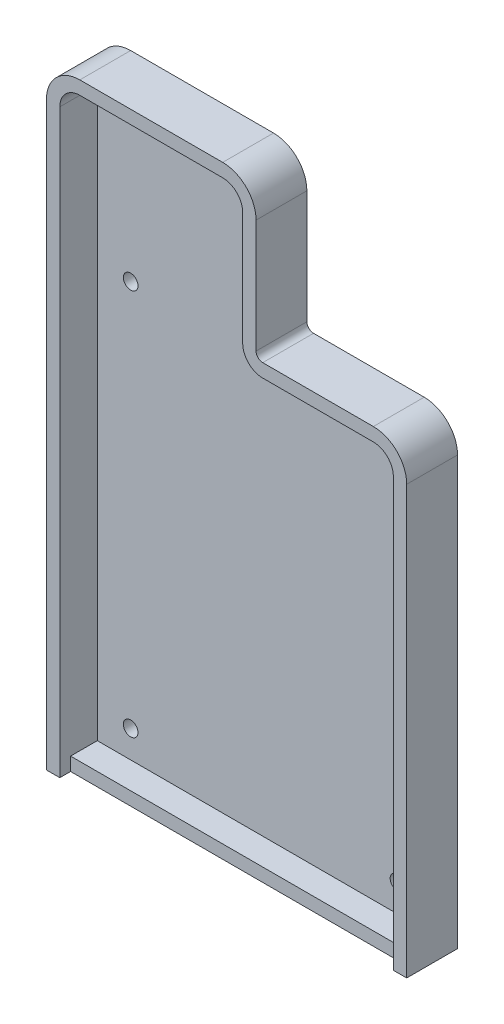
SolidWorks part; units mm, degrees
ref_plane "Front Plane" through (0, 0, 0) normal (0, 0, 1) x (1, 0, 0)
ref_plane "Top Plane" through (0, 0, 0) normal (0, 1, 0) x (1, 0, 0)
ref_plane "Right Plane" through (0, 0, 0) normal (1, 0, 0) x (0, 0, -1)
ref_plane "Plane1" through (200, 247, 0) normal (0, 1, 0) x (1, 0, 0)
sketch "Sketch3" plane through (0, 0, 0) normal (0, 0, 1) x (1, 0, 0)
  line L0 (200, 60) -> (200, 247) construction
  line L1 (200, 161.9071) -> (250, 161.9071)
  line L2 (250, 224) -> (250, 60) construction
  line L3 (227.416, 247) -> (227.416, 230) construction
  line L4 (230.416, 227) -> (247, 227) construction
  line L5 (227.416, 247) -> (227.416, 230)
  line L6 (230.416, 227) -> (247, 227)
  line L7 (203, 250) -> (224.416, 250) construction
  line L8 (250, 224) -> (250, 161.9071)
  line L9 (200, 161.9071) -> (200, 247)
  line L10 (203, 250) -> (224.416, 250)
  line L11 (252, 224.0004) -> (252, 159.9071)
  line L12 (198, 159.9071) -> (252, 159.9071)
  line L13 (198, 159.9071) -> (198, 247.0004)
  line L14 (202.9996, 252) -> (224.4164, 252)
  line L15 (229.416, 247.0004) -> (229.416, 230.0004)
  line L16 (230.4164, 229) -> (247.0004, 229)
  arc A0 (227.416, 230) -> (230.416, 227) centre (230.4171, 230.0011) ccw construction
  arc A1 (250, 224) -> (247, 227) centre (246.9989, 223.9989) ccw construction
  arc A2 (227.416, 230) -> (230.416, 227) centre (230.4171, 230.0011) ccw
  arc A3 (250, 224) -> (247, 227) centre (246.9989, 223.9989) ccw
  arc A4 (203, 250) -> (200, 247) centre (203.0011, 246.9989) ccw construction
  arc A5 (227.416, 247) -> (224.416, 250) centre (224.4149, 246.9989) ccw construction
  arc A6 (203, 250) -> (200, 247) centre (203.0011, 246.9989) ccw
  arc A7 (227.416, 247) -> (224.416, 250) centre (224.4149, 246.9989) ccw
  arc A8 (202.9996, 252) -> (198, 247.0004) centre (203.0011, 246.9989) ccw
  arc A9 (229.416, 247.0004) -> (224.4164, 252) centre (224.4149, 246.9989) ccw
  arc A10 (229.416, 230.0004) -> (230.4164, 229) centre (230.4171, 230.0011) ccw
  arc A11 (252, 224.0004) -> (247.0004, 229) centre (246.9989, 223.9989) ccw
  point P13 (0, 0)
  dimension "D1" = 2
sketch "Sketch5" plane through (0, 0, -1.6154) normal (0, 0, -1) x (-1, 0, 0)
  line L0 (-200, 161.9071) -> (-250, 161.9071) construction
  line L1 (-200, 161.9071) -> (-200, 247) construction
  line L2 (-203, 250) -> (-224.416, 250) construction
  line L3 (-227.416, 247) -> (-227.416, 230) construction
  line L4 (-230.416, 227) -> (-247, 227) construction
  line L5 (-250, 224) -> (-250, 161.9071) construction
  line L6 (-200, 161.9071) -> (-250, 161.9071)
  line L7 (-200, 161.9071) -> (-200, 247)
  line L8 (-203, 250) -> (-224.416, 250)
  line L9 (-227.416, 247) -> (-227.416, 230)
  line L10 (-230.416, 227) -> (-247, 227)
  line L11 (-250, 224) -> (-250, 161.9071)
  arc A0 (-200, 247) -> (-203, 250) centre (-203.0011, 246.9989) ccw construction
  arc A1 (-224.416, 250) -> (-227.416, 247) centre (-224.4149, 246.9989) ccw construction
  arc A2 (-230.416, 227) -> (-227.416, 230) centre (-230.4171, 230.0011) ccw construction
  arc A3 (-247, 227) -> (-250, 224) centre (-246.9989, 223.9989) ccw construction
  arc A4 (-200, 247) -> (-203, 250) centre (-203.0011, 246.9989) ccw
  arc A5 (-224.416, 250) -> (-227.416, 247) centre (-224.4149, 246.9989) ccw
  arc A6 (-230.416, 227) -> (-227.416, 230) centre (-230.4171, 230.0011) ccw
  arc A7 (-247, 227) -> (-250, 224) centre (-246.9989, 223.9989) ccw
extrude "Boss-Extrude1" add sketch "Sketch3" against normal blind 7.62
extrude "Boss-Extrude2" add sketch "Sketch5" along normal up to vertex (6.0046 mm away) separate body
sketch "Sketch9" plane through (0, 0, -1.6154) normal (0, 0, 1) x (1, 0, 0)
  line L0 (200, 161.9071) -> (250, 161.9071) construction
  line L1 (250, 161.9071) -> (250, 224) construction
  line L2 (247, 227) -> (230.416, 227) construction
  line L3 (227.416, 230) -> (227.416, 247) construction
  line L4 (224.416, 250) -> (203, 250) construction
  line L5 (200, 247) -> (200, 161.9071) construction
  line L6 (200, 161.9071) -> (250, 161.9071)
  line L7 (250, 161.9071) -> (250, 224)
  line L8 (247, 227) -> (230.416, 227)
  line L9 (227.416, 230) -> (227.416, 247)
  line L10 (224.416, 250) -> (203, 250)
  line L11 (200, 247) -> (200, 161.9071)
  arc A0 (250, 224) -> (247, 227) centre (246.9989, 223.9989) ccw construction
  arc A1 (227.416, 230) -> (230.416, 227) centre (230.4171, 230.0011) ccw construction
  arc A2 (227.416, 247) -> (224.416, 250) centre (224.4149, 246.9989) ccw construction
  arc A3 (203, 250) -> (200, 247) centre (203.0011, 246.9989) ccw construction
  arc A4 (250, 224) -> (247, 227) centre (246.9989, 223.9989) ccw
  arc A5 (227.416, 230) -> (230.416, 227) centre (230.4171, 230.0011) ccw
  arc A6 (227.416, 247) -> (224.416, 250) centre (224.4149, 246.9989) ccw
  arc A7 (203, 250) -> (200, 247) centre (203.0011, 246.9989) ccw
sketch "Sketch11" plane through (0, 159.9071, 0) normal (0, -1, 0) x (1, 0, 0)
  line L0 (200, 0) -> (200, -1.6154)
  line L1 (200, -1.6154) -> (250, -1.6154)
  line L2 (250, -1.6154) -> (250, 0)
  line L3 (250, 0) -> (200, 0)
sketch "Sketch12" plane through (0, 0, -1.6154) normal (0, 0, -1) x (-1, 0, 0)
  circle A0 centre (-205, 224) radius 1.1 construction
  circle A1 centre (-225, 224) radius 1.1 construction
  circle A2 centre (-205, 166) radius 1.1 construction
  circle A3 centre (-245, 166) radius 1.1 construction
  circle A4 centre (-205, 224) radius 1.1
  circle A5 centre (-225, 224) radius 1.1
  circle A6 centre (-205, 166) radius 1.1
  circle A7 centre (-245, 166) radius 1.1
  circle A8 centre (-245, 166) radius 2.1
  circle A9 centre (-205, 166) radius 2.1
  circle A10 centre (-225, 224) radius 2.1
  circle A11 centre (-205, 224) radius 2.1
  dimension "D1" = 1
sketch "Sketch13" plane through (0, 0, -1.6154) normal (0, 0, -1) x (-1, 0, 0)
  circle A0 centre (-225, 224) radius 1.1 construction
  circle A1 centre (-205, 224) radius 1.1 construction
  circle A2 centre (-205, 166) radius 1.1 construction
  circle A3 centre (-245, 166) radius 1.1 construction
  circle A4 centre (-225, 224) radius 1.1
  circle A5 centre (-205, 224) radius 1.1
  circle A6 centre (-205, 166) radius 1.1
  circle A7 centre (-245, 166) radius 1.1
extrude "Boss-Extrude5" add sketch "Sketch12" along normal up to surface (6.0046 mm away) up to face at (225.9664, 222.7056, -7.62)
extrude "Cut-Extrude5" cut sketch "Sketch13" along normal up to surface (6.0046 mm away) up to face at (226.4493, 223.2714, -7.62)
extrude "Cut-Extrude6" cut sketch "Sketch11" against normal up to surface (2 mm away) up to face at (225, 161.9071, -0.8077)
extrude "Cut-Extrude7" cut sketch "Sketch9" against normal offset from surface (4.0046 mm away) 2 up to face at (246.1, 166, -7.62)
